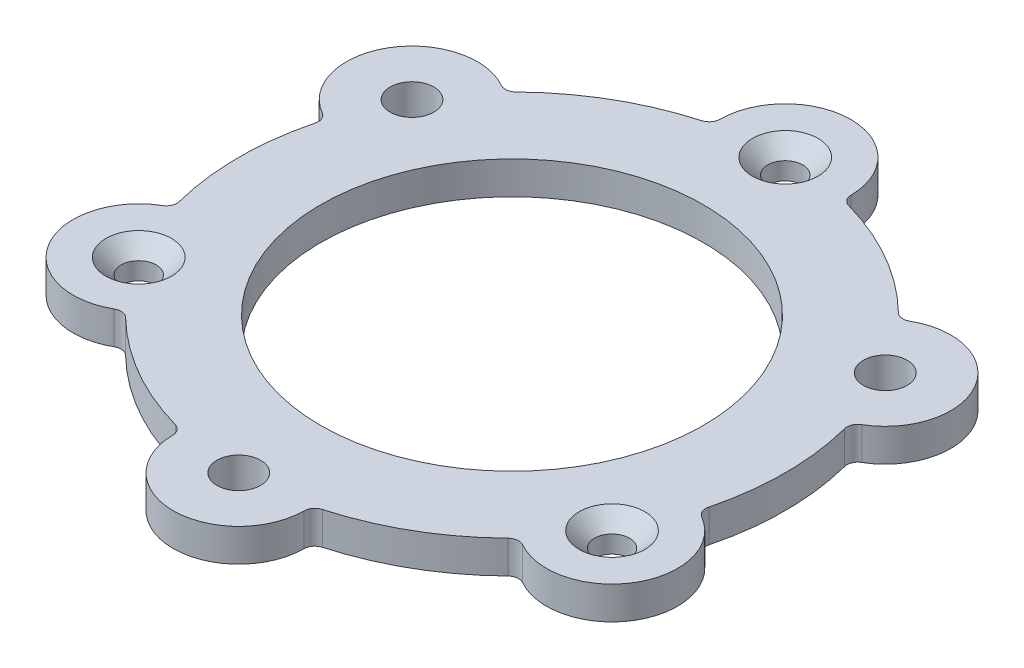
SolidWorks part; units mm, degrees
material "Delrin 2700 NC010, Low Viscosity Acetal Copolymer (SS)"
ref_plane "Front" through (0, 0, 0) normal (0, 0, 1) x (1, 0, 0)
ref_plane "Top" through (0, 0, 0) normal (0, 1, 0) x (1, 0, 0)
ref_plane "Right" through (0, 0, 0) normal (1, 0, 0) x (0, 0, -1)
sketch "Sketch1" plane through (0, 0, 0) normal (0, 1, 0) x (1, 0, 0)
  line L0 (0, 0) -> (-10.8253, -6.25) construction
  line L5 (0, 0) -> (0, -12.5) construction
  line L8 (3, 0) -> (3, -12.5)
  line L9 (-3, 0) -> (-3, -12.5)
  line L10 (1.5, -2.5981) -> (-9.3253, -8.8481)
  line L11 (-1.5, 2.5981) -> (-12.3253, -3.6519)
  line L12 (0, 0) -> (-10.8253, 6.25) construction
  line L13 (-1.5, -2.5981) -> (-12.3253, 3.6519)
  line L14 (1.5, 2.5981) -> (-9.3253, 8.8481)
  line L15 (0, 0) -> (0, 12.5) construction
  line L16 (-3, 0) -> (-3, 12.5)
  line L17 (3, 0) -> (3, 12.5)
  line L18 (0, 0) -> (10.8253, 6.25) construction
  line L19 (-1.5, 2.5981) -> (9.3253, 8.8481)
  line L20 (1.5, -2.5981) -> (12.3253, 3.6519)
  line L21 (0, 0) -> (10.8253, -6.25) construction
  line L22 (1.5, 2.5981) -> (12.3253, -3.6519)
  line L23 (-1.5, -2.5981) -> (9.3253, -8.8481)
  circle A1 centre (0, 0) radius 7.5
  arc A11 (3, 0) -> (-3, 0) centre (0, 0) ccw
  arc A12 (-3, -12.5) -> (3, -12.5) centre (0, -12.5) ccw
  circle A13 centre (0, -12.5) radius 1
  arc A15 (1.5, -2.5981) -> (-1.5, 2.5981) centre (0, 0) ccw
  arc A16 (-12.3253, -3.6519) -> (-9.3253, -8.8481) centre (-10.8253, -6.25) ccw
  circle A17 centre (-10.8253, 6.25) radius 1
  arc A18 (-1.5, -2.5981) -> (1.5, 2.5981) centre (0, 0) ccw
  arc A19 (-9.3253, 8.8481) -> (-12.3253, 3.6519) centre (-10.8253, 6.25) ccw
  circle A20 centre (0, 0) radius 8.75
  circle A21 centre (0, 0) radius 12.5
  arc A23 (-3, 0) -> (3, 0) centre (0, 0) ccw
  arc A24 (3, 12.5) -> (-3, 12.5) centre (0, 12.5) ccw
  circle A25 centre (10.8253, 6.25) radius 1
  arc A26 (-1.5, 2.5981) -> (1.5, -2.5981) centre (0, 0) ccw
  arc A27 (12.3253, 3.6519) -> (9.3253, 8.8481) centre (10.8253, 6.25) ccw
  arc A29 (1.5, 2.5981) -> (-1.5, -2.5981) centre (0, 0) ccw
  arc A30 (9.3253, -8.8481) -> (12.3253, -3.6519) centre (10.8253, -6.25) ccw
  circle A31 centre (-10.8253, -6.25) radius 1 [skipped]
  circle A32 centre (10.8253, -6.25) radius 1 [skipped]
  circle A33 centre (0, 12.5) radius 1 [skipped]
  point P6 (-5.4127, -3.125)
  point P10 (0, -6.25)
  point P22 (-5.4127, 3.125)
  point P30 (0, -15.5)
  point P32 (0, 6.25)
  point P40 (5.4127, 3.125)
  point P48 (5.4127, -3.125)
  dimension "D2" = 15
  dimension "D3" = 6
  dimension "D5" = 25
  dimension "D6" = 3
  dimension "D7" = 2
  dimension "D4" = 17.5
  dimension "D8" = 12.5
extrude "Boss-Extrude1" add sketch "Sketch1" along normal blind 1.5
sketch "Sketch2" plane through (0, 1.5, 0) normal (0, 1, 0) x (1, 0, 0)
  line L0 (0, 0) -> (0, 12.5) construction
  line L1 (0, 0) -> (10.8253, -6.25) construction
  line L2 (0, 0) -> (-10.8253, -6.25) construction
  dimension "D1" = 12.5
  dimension "D2" = 3
hole_wizard "CSK for M3 SFHCS1" positions "3DSketch1" profile "Sketch5" countersink size "M3" standard "ANSI Metric"
sketch3d "3DSketch1"
  point P0 (-10.8253, 1.5, 6.25)
  point P3 (0, 1.5, -12.5)
  point P6 (10.8253, 1.5, 6.25)
sketch "Sketch5" plane through (-10.8253, 1.5, 6.25) normal (1, 0, 0) x (0, 0, 1)
  line L0 (0, 0) -> (0, 7.9807)
  line L1 (0, 7.9807) -> (0.8, 7.5)
  line L2 (0.8, 7.5) -> (0.8, 0.7)
  line L3 (0.8, 0.7) -> (1.5, 0)
  line L5 (1.5, 0) -> (0, 0)
  line L6 (-0.8, 0.7) -> (-1.5, 0) construction
  line L10 (0, 7.9807) -> (-0.8, 7.5) construction
  line L11 (0, -6.35) -> (0, 107.95) construction
  dimension "Hole Dia." = 1.6
  dimension "Hole Depth" = 7.5
  dimension "Near C'Sink Dia." = 3
  dimension "Near C'Sink Angle" = 90
  dimension "Drill Angle" = 118
fillet "Fillet1" radius 0.5 12 edges at (-3, 0.75, 12.1347) (3, 0.75, 12.1347) (9.0089, 0.75, 8.6654) (12.0089, 0.75, 3.4693) (12.0089, 0.75, -3.4693) (9.0089, 0.75, -8.6654) (3, 0.75, -12.1347) (-3, 0.75, -12.1347) (-9.0089, 0.75, -8.6654) (-12.0089, 0.75, -3.4693) (-12.0089, 0.75, 3.4693) (-9.0089, 0.75, 8.6654)
